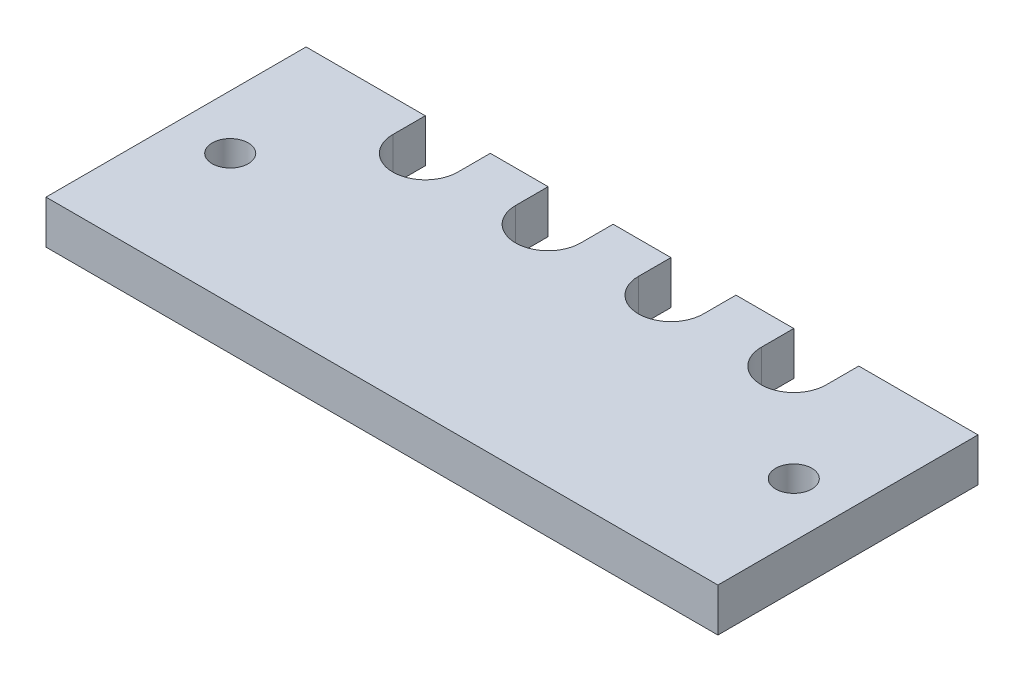
SolidWorks part; units mm, degrees
ref_plane "Front Plane" through (0, 0, 0) normal (0, 0, 1) x (1, 0, 0)
ref_plane "Top Plane" through (0, 0, 0) normal (0, 1, 0) x (1, 0, 0)
ref_plane "Right Plane" through (0, 0, 0) normal (1, 0, 0) x (0, 0, -1)
sketch "Sketch1" plane through (0, 0, 0) normal (0, 1, 0) x (1, 0, 0)
  line L0 (0, -9) -> (0, 9) construction
  line L1 (-23.25, -9) -> (23.25, -9)
  line L2 (-23.25, -9) -> (-23.25, 9)
  line L3 (-23.25, 9) -> (23.25, 9)
  line L4 (23.25, -9) -> (23.25, 9)
  line L5 (-23.25, -9) -> (23.25, 9) construction
  line L6 (-23.25, 9) -> (23.25, -9) construction
  line L7 (15.75, -9) -> (15.75, 9) construction
  line L8 (15.75, -9) -> (23.25, 9) construction
  line L9 (12.75, -9) -> (12.75, 9) construction
  line L10 (4.25, -9) -> (4.25, 9) construction
  line L11 (15, 6.75) -> (15, 9)
  line L12 (10.5, 6.75) -> (10.5, 9)
  line L13 (2, 6.75) -> (2, 9)
  line L14 (6.5, 6.75) -> (6.5, 9)
  line L15 (-6.5, 6.75) -> (-6.5, 9)
  line L16 (-2, 6.75) -> (-2, 9)
  line L17 (-15, 6.75) -> (-15, 9)
  line L18 (-10.5, 6.75) -> (-10.5, 9)
  circle A0 centre (19.5, 0) radius 1.25
  circle A1 centre (-19.5, 0) radius 1.25
  arc A2 (10.5, 6.75) -> (15, 6.75) centre (12.75, 6.75) ccw
  arc A3 (2, 6.75) -> (6.5, 6.75) centre (4.25, 6.75) ccw
  arc A4 (-6.5, 6.75) -> (-2, 6.75) centre (-4.25, 6.75) ccw
  arc A5 (-15, 6.75) -> (-10.5, 6.75) centre (-12.75, 6.75) ccw
  point P0 (0, 0)
  point P9 (0, 0)
  point P12 (15.75, 0)
  point P21 (0, 0)
  dimension "D4" = 2.5
  dimension "D7" = 4.5
  dimension "D1" = 46.5
  dimension "D2" = 18
  dimension "D3" = 7.5
  dimension "D5" = 8.5
  dimension "D6" = 3
  dimension "D8" = 4
extrude "Boss-Extrude1" add sketch "Sketch1" along normal blind 3 contours A5 L17 L3 L2 L1 L4 L11 A2 L12 L14 A3 L13 L16 A4 L15 L18 A0 A1
